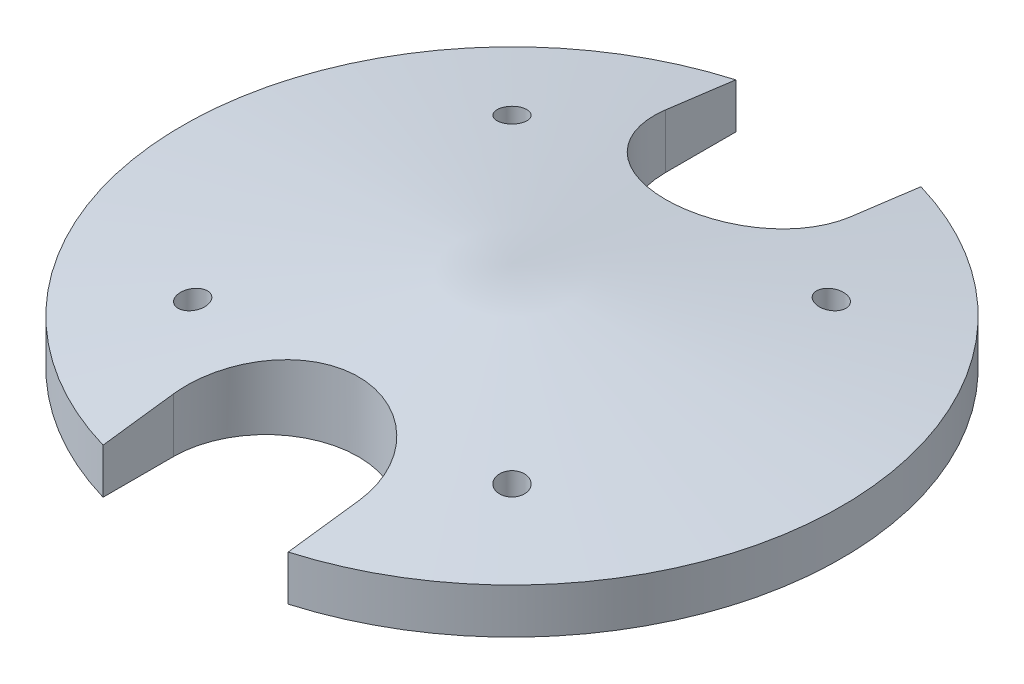
SolidWorks part; units mm, degrees
ref_plane "Front Plane" through (0, 0, 0) normal (0, 0, 1) x (1, 0, 0)
ref_plane "Top Plane" through (0, 0, 0) normal (0, 1, 0) x (1, 0, 0)
ref_plane "Right Plane" through (0, 0, 0) normal (1, 0, 0) x (0, 0, -1)
sketch "Sketch2" plane through (0, 0, 0) normal (1, 0, 0) x (0, 0, -1)
  line L0 (0, 0) -> (73, 0)
  line L1 (73, 0) -> (73, 10)
  line L2 (0, 20) -> (0, 0)
  line L4 (0, 20) -> (73, 10)
  dimension "D1" = 73
  dimension "D2" = 20
  dimension "D3" = 10
revolve "Revolve1" add sketch "Sketch2" angle 360 about L0
sketch "Sketch4" plane through (0, 0, 0) normal (0, -1, 0) x (1, 0, 0)
  line L0 (0, 0) -> (0, 35.7953) construction
  line L1 (0, 0) -> (-35.3553, 35.3553) construction
  circle A0 centre (-35.3553, 35.3553) radius 1.7
  circle A1 centre (35.3553, 35.3553) radius 1.7
  circle A2 centre (35.3553, -35.3553) radius 1.7
  circle A3 centre (-35.3553, -35.3553) radius 1.7
  point P14 (0, 0)
  dimension "D3" = 4
  dimension "D1" = 45
  dimension "D2" = 50
extrude "Cut-Extrude1" cut sketch "Sketch4" against normal through all
sketch "Sketch5" plane through (0, 0, 0) normal (0, -1, 0) x (1, 0, 0)
  line L0 (0, 0) -> (0, 75) construction
  line L1 (-20.5, 54.5) -> (-20.5, 75)
  line L2 (-20.5, 75) -> (0, 75)
  line L3 (0, 75) -> (20.5, 75)
  line L4 (20.5, 75) -> (20.5, 54.5)
  arc A0 (-20.5, 54.5) -> (20.5, 54.5) centre (0, 54.5) ccw
  dimension "D2" = 41
  dimension "D1" = 75
extrude "Cut-Extrude2" cut sketch "Sketch5" against normal through all
mirror "Mirror1" about plane through (0, 0, 0) normal (0, 0, 1) of "Cut-Extrude2"
ref_plane "Plane1" through (0, 5, 0) normal (0, 1, 0) x (1, 0, 0)
sketch "Sketch9" plane through (0, 5, 0) normal (0, 1, 0) x (1, 0, 0)
  circle A0 centre (-35.3553, -35.3553) radius 3
  circle A1 centre (-35.3553, 35.3553) radius 3
  circle A2 centre (35.3553, 35.3553) radius 3
  circle A3 centre (35.3553, -35.3553) radius 3
  point P12 (0, 0)
  dimension "D1" = 6
  dimension "D2" = 4
extrude "Cut-Extrude3" cut sketch "Sketch9" along normal through all
